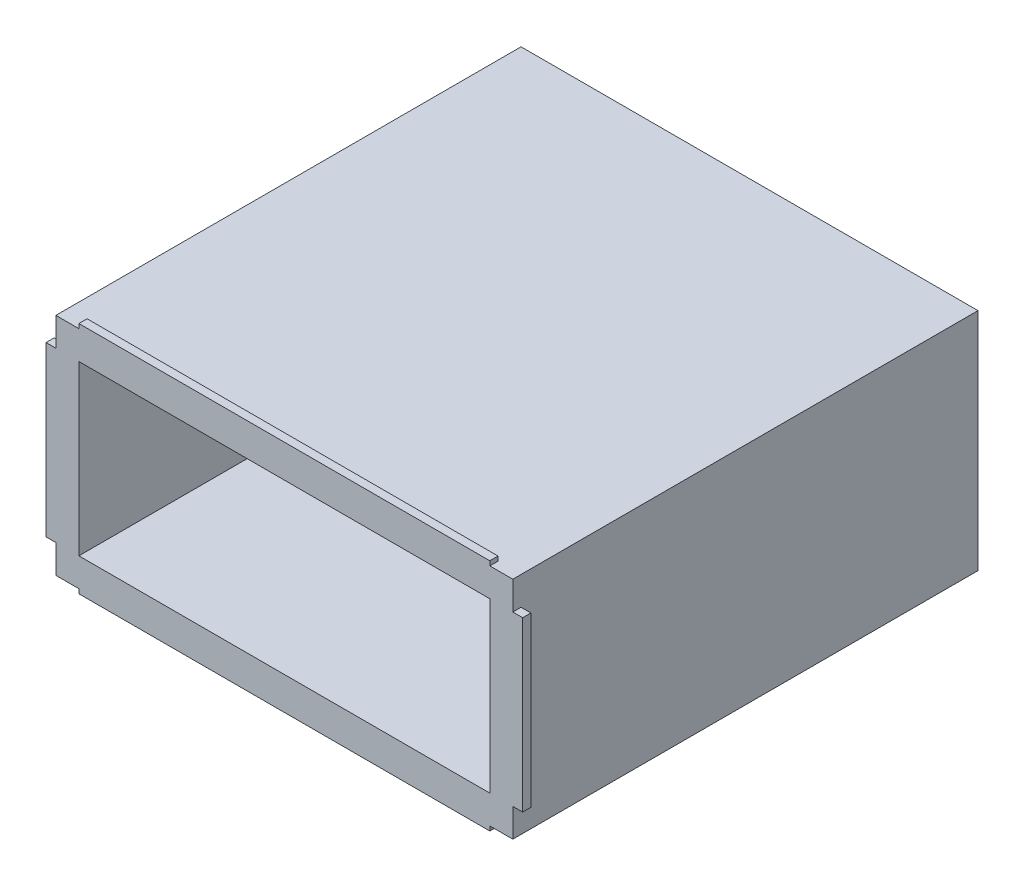
SolidWorks part; units mm, degrees
material "Nickel"
ref_plane "Front Plane" through (0, 0, 0) normal (0, 0, 1) x (1, 0, 0)
ref_plane "Top Plane" through (0, 0, 0) normal (0, 1, 0) x (1, 0, 0)
ref_plane "Right Plane" through (0, 0, 0) normal (1, 0, 0) x (0, 0, -1)
sketch "Sketch1" plane through (0, 0, 0) normal (0, 0, 1) x (1, 0, 0)
  line L1 (-6.95, -3.425) -> (6.95, -3.425)
  line L2 (-6.95, -3.425) -> (-6.95, 3.425)
  line L3 (-6.95, 3.425) -> (6.95, 3.425)
  line L4 (6.95, -3.425) -> (6.95, 3.425)
  line L5 (-6.95, -3.425) -> (6.95, 3.425) construction
  line L6 (-6.95, 3.425) -> (6.95, -3.425) construction
  point P0 (0, 0)
  dimension "D1" = 13.9
  dimension "D2" = 6.85
extrude "Boss-Extrude1" add sketch "Sketch1" along normal blind 14.15
sketch "Sketch2" plane through (0, 0, 14.15) normal (0, 0, 1) x (1, 0, 0)
  line L1 (-6.25, -2.56) -> (6.25, -2.56)
  line L2 (-6.25, -2.56) -> (-6.25, 2.56)
  line L3 (-6.25, 2.56) -> (6.25, 2.56)
  line L4 (6.25, -2.56) -> (6.25, 2.56)
  line L5 (-6.25, -2.56) -> (6.25, 2.56) construction
  line L6 (-6.25, 2.56) -> (6.25, -2.56) construction
  point P0 (0, 0)
  dimension "D1" = 12.5
  dimension "D2" = 5.12
extrude "Cut-Extrude1" cut sketch "Sketch2" against normal blind 13
sketch "Sketch4" plane through (0, 3.425, 0) normal (0, 1, 0) x (1, 0, 0)
  line L1 (-6.25, -14.15) -> (6.25, -14.15)
  line L2 (-6.25, -14.15) -> (-6.25, -13.9)
  line L3 (-6.25, -13.9) -> (6.25, -13.9)
  line L4 (6.25, -14.15) -> (6.25, -13.9)
  line L5 (6.95, 0) -> (-6.95, 0) construction
  point P5 (0, -13.9)
  point P8 (0, 0)
  dimension "D1" = 0.25
  dimension "D2" = 12.5
extrude "Boss-Extrude2" add sketch "Sketch4" along normal blind 0.135
mirror "Mirror1" about plane through (0, 0, 0) normal (0, 1, 0) of "Boss-Extrude2"
sketch "Sketch5" plane through (6.95, 0, 0) normal (1, 0, 0) x (0, 0, -1)
  line L0 (-14.15, -3.425) -> (-14.15, 3.425) construction
  line L1 (-13.9, 2.56) -> (-14.15, 2.56)
  line L2 (-13.9, 2.56) -> (-13.9, -2.56)
  line L3 (-13.9, -2.56) -> (-14.15, -2.56)
  line L4 (-14.15, 2.56) -> (-14.15, -2.56)
  point P4 (-13.9, 0)
  point P7 (0, 0)
  point P8 (0, 0)
  point P10 (0, 0)
  dimension "D1" = 5.12
  dimension "D2" = 0.25
extrude "Boss-Extrude3" add sketch "Sketch5" along normal blind 0.3
mirror "Mirror2" about plane through (0, 0, 0) normal (1, 0, 0) of "Boss-Extrude3"
